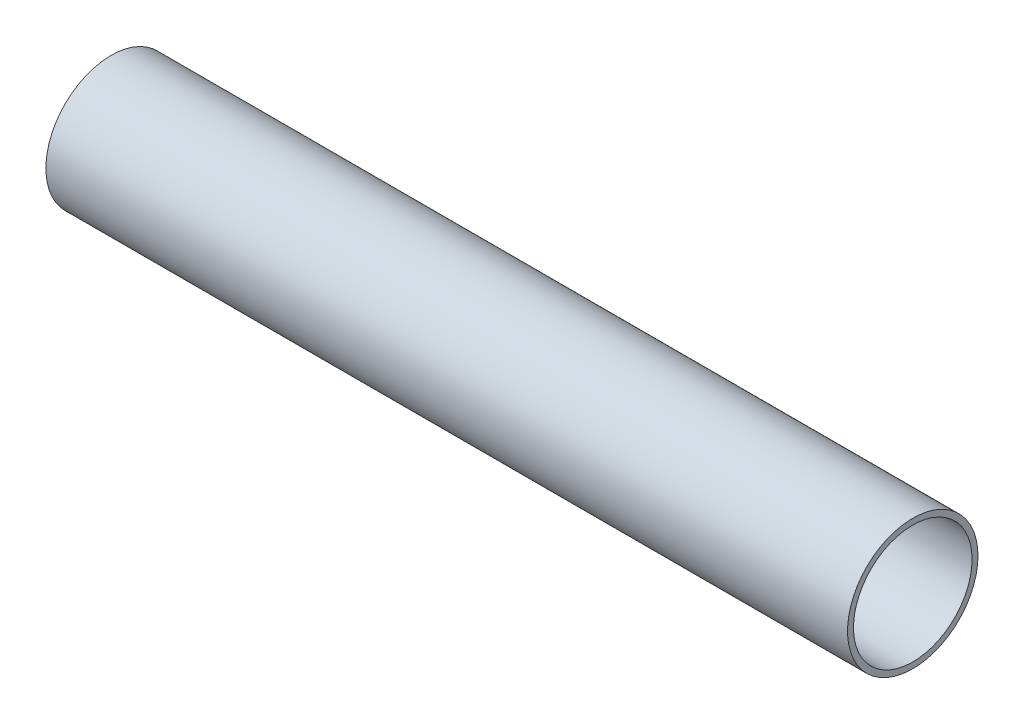
SolidWorks part; units mm, degrees
ref_plane "Płaszczyzna przednia" through (0, 0, 0) normal (0, 0, 1) x (1, 0, 0)
ref_plane "Płaszczyzna górna" through (0, 0, 0) normal (0, 1, 0) x (1, 0, 0)
ref_plane "Płaszczyzna prawa" through (0, 0, 0) normal (1, 0, 0) x (0, 0, -1)
sketch "Szkic1" plane through (0, 0, 0) normal (1, 0, 0) x (0, 0, -1)
  circle A0 centre (0, 0) radius 25
  circle A1 centre (0, 0) radius 27.5
  dimension "D1" = 50
  dimension "D2" = 55
extrude "Dodanie-wyciągnięcie1" add sketch "Szkic1" against normal blind 338
